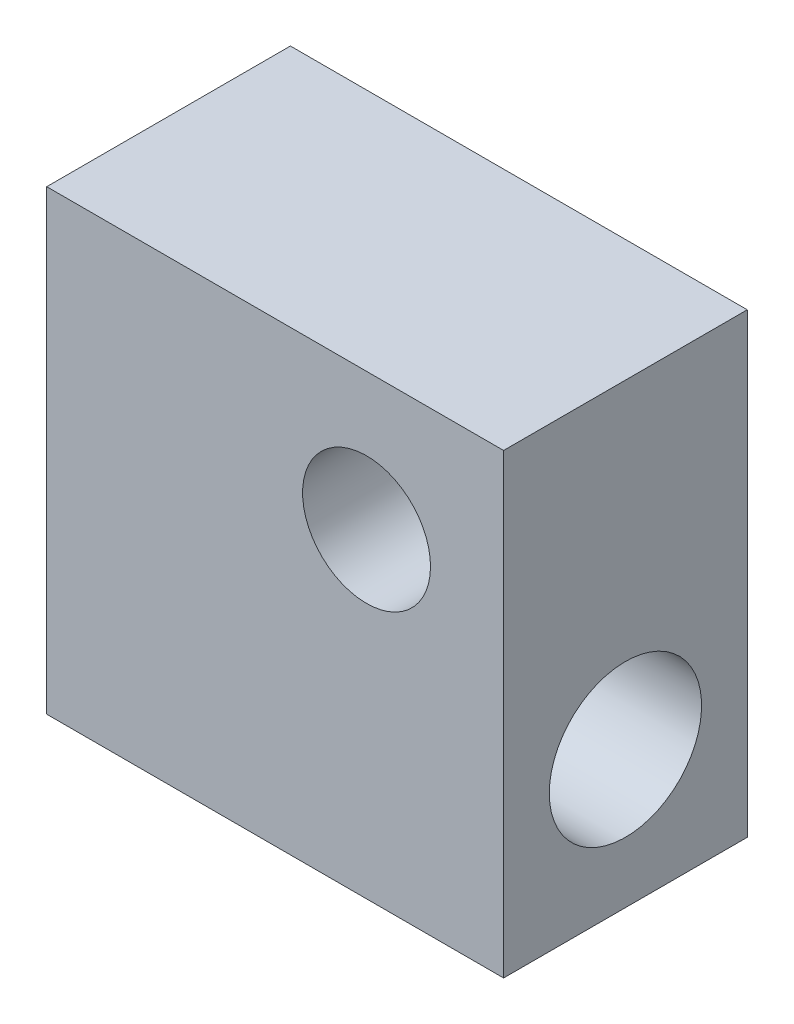
SolidWorks part; units mm, degrees
ref_plane "Front Plane" through (0, 0, 0) normal (0, 0, 1) x (1, 0, 0)
ref_plane "Top Plane" through (0, 0, 0) normal (0, 1, 0) x (1, 0, 0)
ref_plane "Right Plane" through (0, 0, 0) normal (1, 0, 0) x (0, 0, -1)
sketch "Sketch1" plane through (0, 0, 0) normal (0, 0, 1) x (1, 0, 0)
  line L1 (0, 0) -> (15, 0)
  line L2 (0, 0) -> (0, 15)
  line L3 (0, 15) -> (15, 15)
  line L4 (15, 0) -> (15, 15)
  dimension "D1" = 15
  dimension "D2" = 15
extrude "Boss-Extrude1" add sketch "Sketch1" along normal blind 8
hole_wizard "Tap Drill for M5x0.8 Tap1" positions "Sketch3" profile "Sketch2" hole size "M5x0.8" standard "Ansi Metric" end condition through all
sketch "Sketch3" plane through (0, 0, 8) normal (0, 0, 1) x (1, 0, 0)
  line L0 (15, 0) -> (15, 15) construction
  line L1 (15, 15) -> (0, 15) construction
  point P0 (10.5, 10.5)
  dimension "D1" = 4.5
  dimension "D2" = 4.5
sketch "Sketch2" plane through (10.5, 10.5, 8) normal (1, 0, 0) x (0, -1, 0)
  line L0 (0, 0) -> (0, 8)
  line L1 (0, 8) -> (2.1, 8)
  line L2 (2.1, 8) -> (2.1, 0)
  line L5 (2.1, 0) -> (0, 0)
  line L11 (0, -6.35) -> (0, 107.95) construction
  dimension "Thru Hole Dia." = 4.2
  dimension "Thru Hole Depth" = 8
hole_wizard "Ø5.0 (5) Diameter Hole1" positions "Sketch5" profile "Sketch4" hole size "Ø5.0" standard "Ansi Metric" end condition through all
sketch "Sketch5" plane through (0, 0, 0) normal (-1, 0, 0) x (0, 0, 1)
  line L0 (4, 0) -> (4, 7.9761) construction
  line L1 (8, 0) -> (0, 0) construction
  point P0 (4, 4.5)
  dimension "D1" = 4.5
sketch "Sketch4" plane through (0, 4.5, 4) normal (0, 1, 0) x (0, 0, 1)
  line L0 (0, 0) -> (0, 15)
  line L1 (0, 15) -> (2.5, 15)
  line L2 (2.5, 15) -> (2.5, 0)
  line L5 (2.5, 0) -> (0, 0)
  line L11 (0, -6.35) -> (0, 107.95) construction
  dimension "Thru Hole Dia." = 5
  dimension "Thru Hole Depth" = 15
